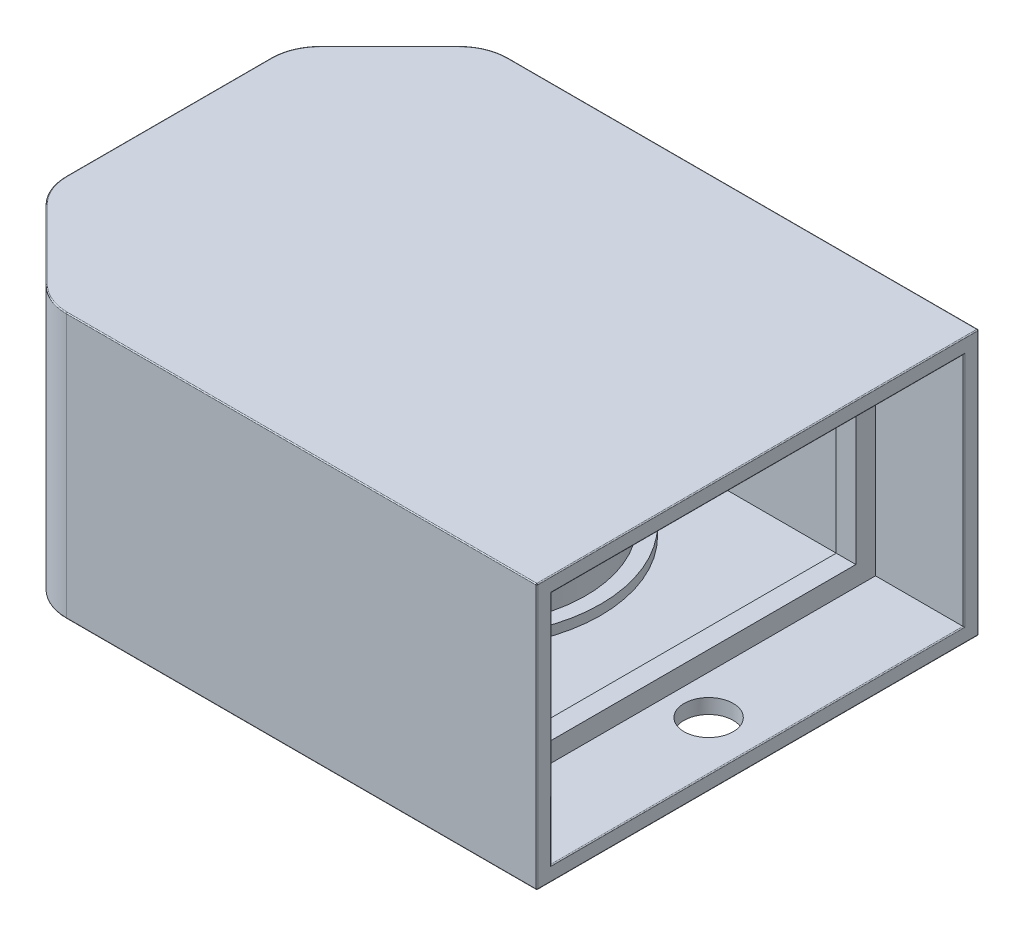
SolidWorks part; units mm, degrees
ref_plane "前视基准面" through (0, 0, 0) normal (0, 0, 1) x (1, 0, 0)
ref_plane "上视基准面" through (0, 0, 0) normal (0, 1, 0) x (1, 0, 0)
ref_plane "右视基准面" through (0, 0, 0) normal (1, 0, 0) x (0, 0, -1)
sketch "草图1" plane through (0, 0, 0) normal (0, 1, 0) x (1, 0, 0)
  line L1 (-30, -22.5) -> (30, -22.5)
  line L2 (-30, -22.5) -> (-30, 22.5)
  line L3 (-30, 22.5) -> (30, 22.5)
  line L4 (30, -22.5) -> (30, 22.5)
  line L5 (-30, -22.5) -> (30, 22.5) construction
  line L6 (-30, 22.5) -> (30, -22.5) construction
  point P0 (0, 0)
  dimension "D1" = 45
  dimension "D2" = 60
extrude "凸台-拉伸1" add sketch "草图1" along normal mid plane 27
chamfer "倒角1" distance 10 angle 45 2 edges at (-30, 0, -22.5) (-30, 0, 22.5)
fillet "圆角1" radius 5 4 edges at (-20, 0, -22.5) (-30, 0, -12.5) (-30, 0, 12.5) (-20, 0, 22.5)
shell "抽壳1" thickness 1.5
fillet "圆角2" radius 0.1 26 edges at (30, 0, -21) (30, 12, 0) (30, 0, 21) (30, -12, 0) (30, 0, 22.5) (30, 0, -22.5) (-29.6194, -13.5, -12.3423) (-30, -13.5, 0) (-29.6194, -13.5, 12.3423) (-25, -13.5, 17.5) (-19.8423, -13.5, 22.1194) (6.0355, -13.5, 22.5) (30, -13.5, 0) (6.0355, -13.5, -22.5) (-19.8423, -13.5, -22.1194) (-25, -13.5, -17.5) (30, 13.5, 0) (6.0355, 13.5, 22.5) (-19.8423, 13.5, 22.1194) (-25, 13.5, 17.5) (-29.6194, 13.5, 12.3423) (-30, 13.5, 0) (-29.6194, 13.5, -12.3423) (-25, 13.5, -17.5) (-19.8423, 13.5, -22.1194) (6.0355, 13.5, -22.5)
sketch "草图3" plane through (0, 0, 0) normal (0, 0, 1) x (1, 0, 0)
  line L0 (0, 13.4) -> (0, -13.4) construction
  line L1 (29.9, 13.4) -> (-17.9289, 13.4) construction
  line L2 (-17.9289, -13.4) -> (29.9, -13.4) construction
  line L3 (0, 12) -> (4, 12)
  line L4 (-17.9289, 12) -> (29.9, 12) construction
  line L5 (4, 12) -> (4, 3.5)
  line L6 (4, 3.5) -> (14, 3.5)
  line L7 (14, 3.5) -> (14, 2.5)
  line L8 (14, 2.5) -> (12.5, 2.5)
  line L9 (12.5, 2.5) -> (12.5, -7.5)
  line L10 (12.5, -7.5) -> (14, -7.5)
  line L11 (14, -7.5) -> (14, -8.5)
  line L12 (14, -8.5) -> (4, -8.5)
  line L13 (4, -8.5) -> (4, -12)
  line L14 (-17.9289, -12) -> (29.9, -12) construction
  line L15 (4, -12) -> (0, -12)
  line L16 (0, -12) -> (0, 12)
  dimension "D1" = 1
  dimension "D2" = 1.5
  dimension "D3" = 25
  dimension "D4" = 3.5
  dimension "D5" = 8
  dimension "D6" = 10
revolve "旋转1" add sketch "草图3" angle 360 about L0
ref_plane "基准面1" through (20, 0, 0) normal (1, 0, 0) x (0, 0, -1)
sketch "草图4" plane through (20, 0, 0) normal (1, 0, 0) x (0, 0, -1)
  line L1 (-21, -12) -> (21, -12)
  line L2 (-21, -12) -> (-21, 12)
  line L3 (-21, 12) -> (21, 12)
  line L4 (21, -12) -> (21, 12)
extrude "拉伸-薄壁1" add sketch "草图4" along normal mid plane 2 thin thin type one direction reverse wall 2
sketch "草图5" plane through (0, -13.5, 0) normal (0, -1, 0) x (1, 0, 0)
  circle A0 centre (0, 0) radius 4
  dimension "D1" = 8
extrude "凸台-拉伸2" add sketch "草图5" along normal blind 1
sketch "草图6" plane through (0, -14.5, 0) normal (0, -1, 0) x (1, 0, 0)
  line L1 (4, 0) -> (2, 3.4641)
  line L2 (2, 3.4641) -> (-2, 3.4641)
  line L3 (-2, 3.4641) -> (-4, 0)
  line L4 (-4, 0) -> (-2, -3.4641)
  line L5 (-2, -3.4641) -> (2, -3.4641)
  line L6 (2, -3.4641) -> (4, 0)
  circle A0 centre (0, 0) radius 3.4641 construction
  circle A1 centre (0, 0) radius 4 construction
extrude "凸台-拉伸3" add sketch "草图6" along normal blind 10
sketch "草图7" plane through (0, -12, 0) normal (0, 1, 0) x (1, 0, 0)
  line L0 (30, 22.4) -> (30, -22.4) construction
  circle A0 centre (25, 0) radius 2.5
  dimension "D1" = 5
  dimension "D2" = 5
extrude "切除-拉伸1" cut sketch "草图7" against normal up to next
sketch3d "3D草图1"
  line L0 (25, -13.5, 0) -> (25, -12, 0) construction
  circle A0 centre (25, -12, 0) radius 2.5 construction
  point P0 (27.5, -12, 0)
  point P1 (25, -12, 0)
  point P4 (25, -9.5, 0)
